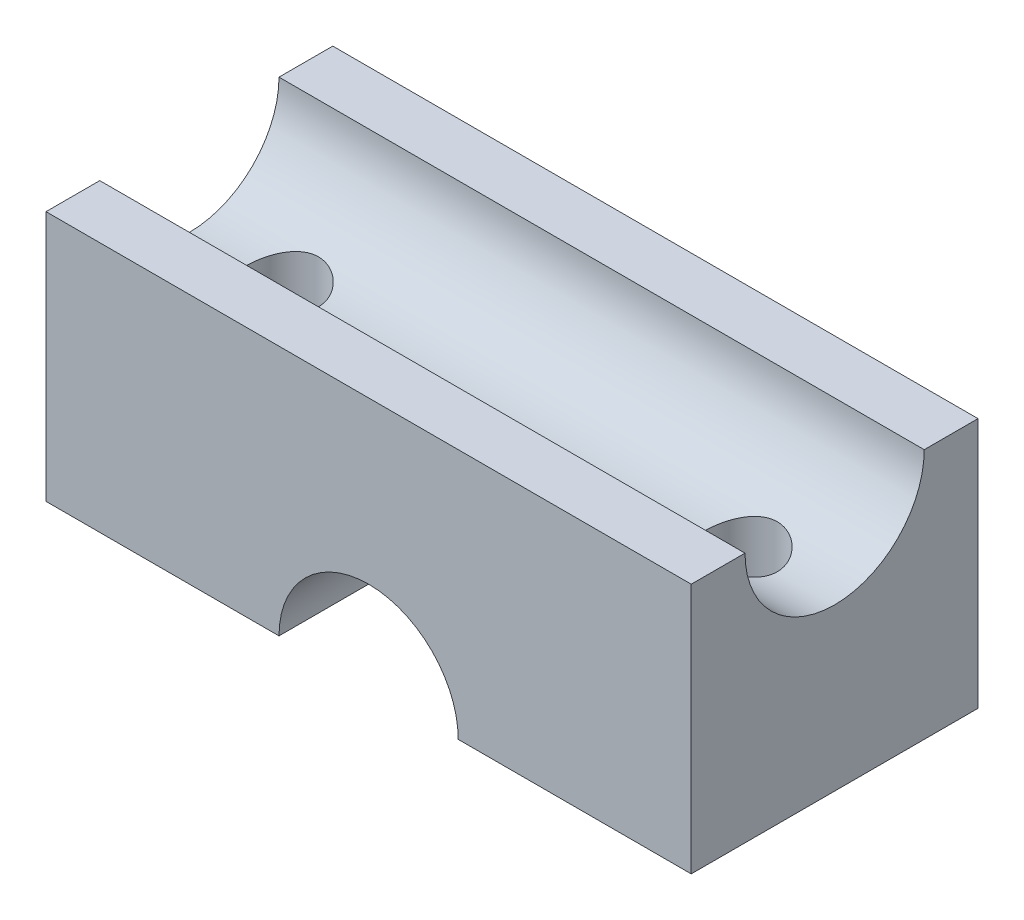
SolidWorks part; units mm, degrees
ref_plane "Front Plane" through (0, 0, 0) normal (0, 0, 1) x (1, 0, 0)
ref_plane "Top Plane" through (0, 0, 0) normal (0, 1, 0) x (1, 0, 0)
ref_plane "Right Plane" through (0, 0, 0) normal (1, 0, 0) x (0, 0, -1)
sketch "Sketch1" plane through (0, 0, 0) normal (1, 0, 0) x (0, 0, -1)
  line L0 (0, 42.5781) -> (0, -17.2656) construction
  line L1 (-20, 0) -> (20, 0)
  line L2 (-20, 0) -> (-20, 35)
  line L3 (-20, 35) -> (-12.5, 35)
  line L4 (20, 0) -> (20, 35)
  line L5 (12.5, 35) -> (20, 35)
  arc A0 (-12.5, 35) -> (12.5, 35) centre (0, 35) ccw
  point P9 (0, 0)
  dimension "D3" = 25
  dimension "D1" = 40
  dimension "D2" = 35
extrude "Boss-Extrude1" add sketch "Sketch1" along normal mid plane 90
sketch "Sketch2" plane through (0, 0, 20) normal (0, 0, 1) x (1, 0, 0)
  circle A0 centre (0, 0) radius 12.5
  dimension "D1" = 25
extrude "Cut-Extrude1" cut sketch "Sketch2" against normal up to next
sketch "Sketch3" plane through (0, 0, 0) normal (0, -1, 0) x (1, 0, 0)
  line L0 (0, -2.0239) -> (0, 4.6839) construction
  circle A0 centre (32, 0) radius 5
  circle A1 centre (-32, 0) radius 5
  point P5 (0, 0)
  point P7 (30.6479, -1.0987)
  dimension "D1" = 10
  dimension "D2" = 32
extrude "Cut-Extrude2" cut sketch "Sketch3" against normal up to next
